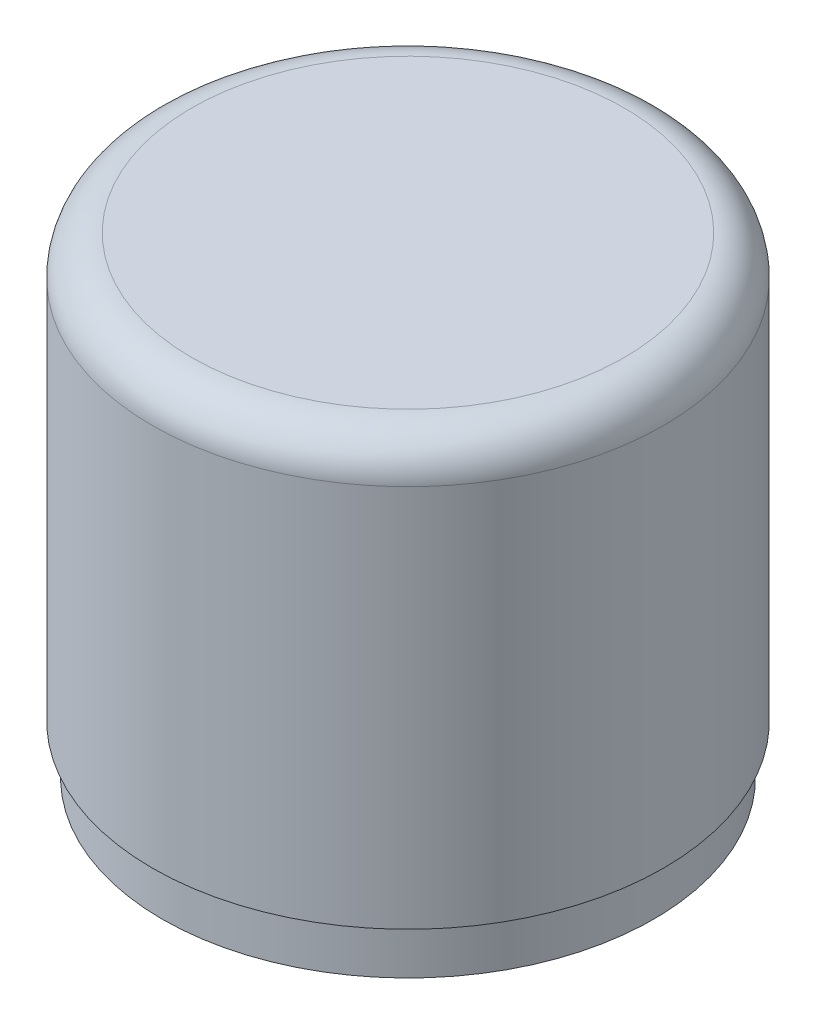
SolidWorks part; units mm, degrees
ref_plane "Front Plane" through (0, 0, 0) normal (0, 0, 1) x (1, 0, 0)
ref_plane "Top Plane" through (0, 0, 0) normal (0, 1, 0) x (1, 0, 0)
ref_plane "Right Plane" through (0, 0, 0) normal (1, 0, 0) x (0, 0, -1)
sketch "Sketch1" plane through (0, 0, 0) normal (0, 1, 0) x (1, 0, 0)
  circle A0 centre (0, 0) radius 26
  dimension "D1" = 52
extrude "Boss-Extrude1" add sketch "Sketch1" along normal blind 43
sketch "Sketch2" plane through (0, 0, 0) normal (0, -1, 0) x (1, 0, 0)
  circle A0 centre (0, 0) radius 25
  dimension "D1" = 50
extrude "Boss-Extrude2" add sketch "Sketch2" along normal blind 5 contours A0
sketch "Sketch3" plane through (0, -5, 0) normal (0, -1, 0) x (1, 0, 0)
  circle A0 centre (0, 0) radius 24.1459
extrude "Cut-Extrude1" cut sketch "Sketch3" against normal blind 44
fillet "Fillet1" radius 4 1 edges at (0, 43, 26)
